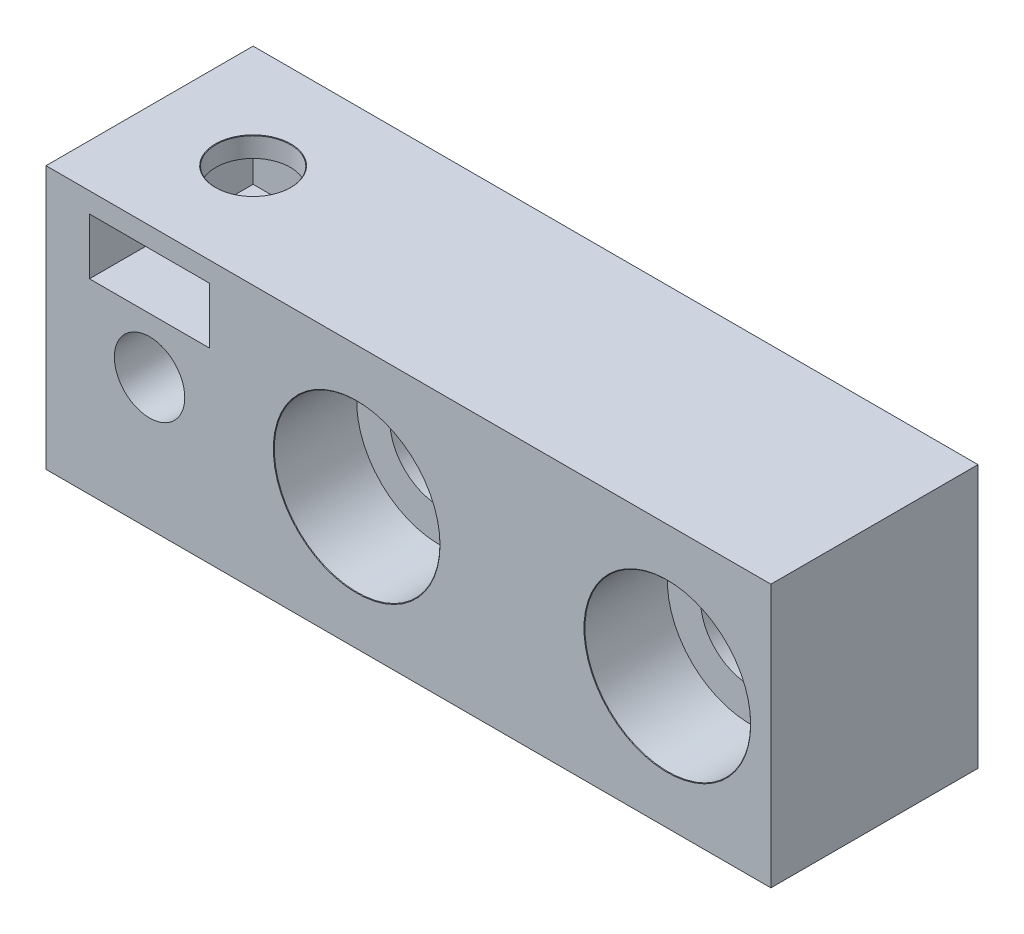
SolidWorks part; units mm, degrees
ref_plane "Front Plane" through (0, 0, 0) normal (0, 0, 1) x (1, 0, 0)
ref_plane "Top Plane" through (0, 0, 0) normal (0, 1, 0) x (1, 0, 0)
ref_plane "Right Plane" through (0, 0, 0) normal (1, 0, 0) x (0, 0, -1)
sketch "Sketch1" plane through (0, 0, 0) normal (0, 0, 1) x (1, 0, 0)
  line L1 (-17.5, 6.35) -> (17.5, 6.35)
  line L2 (-17.5, 6.35) -> (-17.5, -6.35)
  line L3 (-17.5, -6.35) -> (17.5, -6.35)
  line L4 (17.5, 6.35) -> (17.5, -6.35)
  line L5 (-17.5, 6.35) -> (17.5, -6.35) construction
  line L6 (-17.5, -6.35) -> (17.5, 6.35) construction
  point P0 (0, 0)
  dimension "D1" = 12.7
  dimension "D2" = 35
extrude "Boss-Extrude1" add sketch "Sketch1" along normal blind 10
hole_wizard "CBORE for M4 SHCS1" positions "Sketch2" profile "Sketch3" counterbore size "M4" standard "ANSI Metric" end condition through all
sketch "Sketch2" plane through (0, 0, 10) normal (0, 0, 1) x (1, 0, 0)
  line L0 (17.5, -6.35) -> (17.5, 6.35) construction
  point P0 (12.5, 0)
  point P2 (-2.5, 0)
  point P9 (0, 0)
  dimension "D1" = 15
  dimension "D2" = 5
sketch "Sketch3" plane through (12.5, 0, 10) normal (1, 0, 0) x (0, -1, 0)
  line L0 (0, 0) -> (0, 10)
  line L1 (0, 10) -> (2.4, 10)
  line L3 (2.4, 10) -> (2.4, 4)
  line L4 (4, 4) -> (2.4, 4)
  line L5 (4, 4) -> (4, 0.021)
  line L6 (4, 0.021) -> (4.025, 0)
  line L7 (4.025, 0) -> (0, 0)
  line L8 (-4, 0.021) -> (-4.025, 0) construction
  line L11 (0, -6.35) -> (0, 107.95) construction
  dimension "Thru Hole Dia." = 4.8
  dimension "Thru Hole Depth" = 10
  dimension "C'Bore Dia." = 8
  dimension "C'Bore Depth" = 4
  dimension "Near C'Sink Dia." = 8.05
  dimension "Near C'Sink Angle" = 100
sketch "Sketch4" plane through (0, 0, 10) normal (0, 0, 1) x (1, 0, 0)
  line L0 (-17.5, 6.35) -> (-17.5, -6.35) construction
  circle A0 centre (-12.5, 0) radius 1.7
  point P5 (0, 0)
  dimension "D1" = 3.4
  dimension "D2" = 5
extrude "Cut-Extrude1" cut sketch "Sketch4" against normal blind 10
hole_wizard "M3 Clearance Hole1" positions "Sketch5" profile "Sketch6" hole size "M3" standard "ANSI Metric"
sketch "Sketch5" plane through (0, 6.35, 0) normal (0, 1, 0) x (1, 0, 0)
  line L0 (-17.5, -10) -> (-17.5, 0) construction
  point P0 (-12.5, -5)
  point P5 (-17.5, -5)
  dimension "D1" = 5
sketch "Sketch6" plane through (-12.5, 6.35, 5) normal (1, 0, 0) x (0, 0, 1)
  line L0 (0, 0) -> (0, 7)
  line L1 (0, 7) -> (1.8, 5.9185)
  line L2 (1.8, 5.9185) -> (1.8, 0.021)
  line L3 (1.8, 0.021) -> (1.825, 0)
  line L5 (1.825, 0) -> (0, 0)
  line L6 (-1.8, 0.021) -> (-1.825, 0) construction
  line L10 (0, 7) -> (-1.8, 5.9185) construction
  line L11 (0, -6.35) -> (0, 107.95) construction
  dimension "Hole Dia." = 3.6
  dimension "Hole Depth" = 7
  dimension "Near C'Sink Dia." = 3.65
  dimension "Near C'Sink Angle" = 100
  dimension "Drill Angle" = 118
sketch "Sketch7" plane through (0, 0, 10) normal (0, 0, 1) x (1, 0, 0)
  line L0 (-12.5, 1.7) -> (-12.5, 2.67) construction
  line L1 (-15.4, 5.38) -> (-9.6, 5.38)
  line L2 (-15.4, 5.38) -> (-15.4, 2.67)
  line L3 (-15.4, 2.67) -> (-9.6, 2.67)
  line L4 (-9.6, 5.38) -> (-9.6, 2.67)
  line L5 (-12.5, 5.38) -> (-12.5, 6.35) construction
  line L6 (17.5, 6.35) -> (-17.5, 6.35) construction
  line L7 (-17.5, 6.35) -> (-17.5, -6.35) construction
  circle A1 centre (-12.5, 0) radius 1.7 construction
  point P6 (-12.5, 1.7)
  point P13 (-12.8681, 1.6597)
  dimension "D1" = 2.71
  dimension "D2" = 5.8
  dimension "D3" = 5
extrude "Cut-Extrude2" cut sketch "Sketch7" against normal blind 7.9
